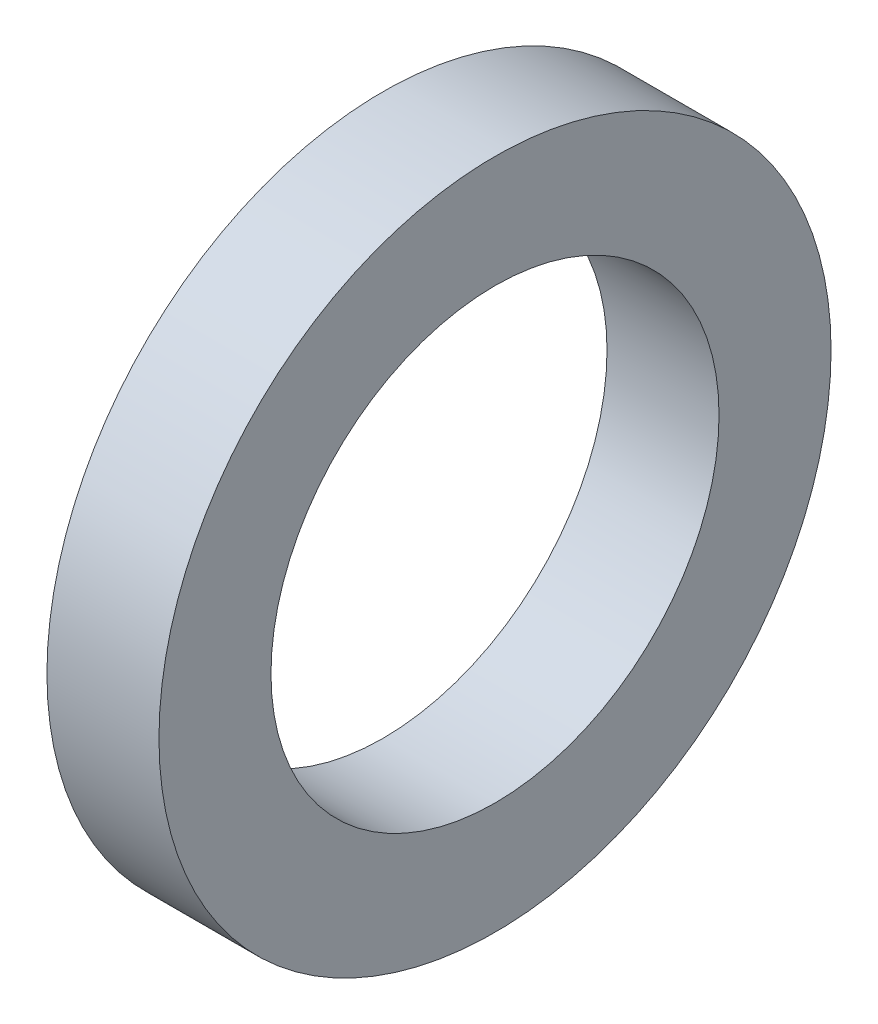
SolidWorks part; units mm, degrees
ref_plane "前视基准面" through (0, 0, 0) normal (0, 0, 1) x (1, 0, 0)
ref_plane "上视基准面" through (0, 0, 0) normal (0, 1, 0) x (1, 0, 0)
ref_plane "右视基准面" through (0, 0, 0) normal (1, 0, 0) x (0, 0, -1)
sketch "草图2" plane through (0, 0, 0) normal (0, 0, 1) x (1, 0, 0)
  line L0 (-0.5, 0) -> (0.5, 0) construction
  line L1 (-0.5, 2) -> (0.5, 2)
  line L2 (-0.5, 2) -> (-0.5, 3)
  line L3 (-0.5, 3) -> (0.5, 3)
  line L4 (0.5, 2) -> (0.5, 3)
  dimension "D1" = 2
  dimension "D2" = 3
  dimension "D3" = 1
revolve "旋转1" add sketch "草图2" angle 360 about L0
